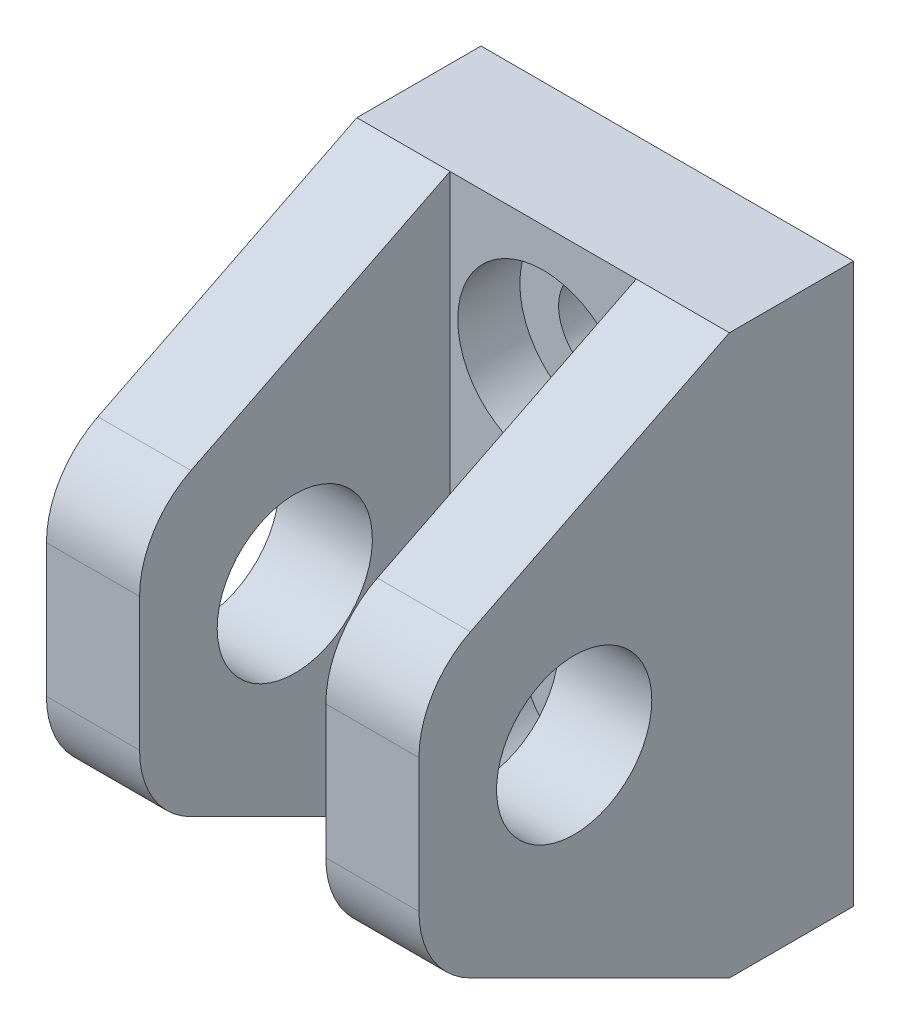
SolidWorks part; units mm, degrees
ref_plane "前视基准面" through (0, 0, 0) normal (0, 0, 1) x (1, 0, 0)
ref_plane "上视基准面" through (0, 0, 0) normal (0, 1, 0) x (1, 0, 0)
ref_plane "右视基准面" through (0, 0, 0) normal (1, 0, 0) x (0, 0, -1)
sketch "草图1" plane through (0, 0, 0) normal (0, 0, 1) x (1, 0, 0)
  line L1 (0, 0) -> (20, 0)
  line L2 (0, 0) -> (0, 18)
  line L3 (0, 18) -> (20, 18)
  line L4 (20, 0) -> (20, 18)
  dimension "D1" = 20
  dimension "D2" = 18
extrude "凸台-拉伸1" add sketch "草图1" along normal blind 4
sketch "草图2" plane through (0, 0, 4) normal (0, 0, 1) x (1, 0, 0)
  line L0 (0, 0) -> (20, 0) construction
  line L1 (16, 0) -> (13, 0)
  line L2 (16, 0) -> (16, 18)
  line L3 (16, 18) -> (13, 18)
  line L4 (13, 0) -> (13, 18)
  line L5 (20, 18) -> (0, 18) construction
  line L6 (20, 0) -> (20, 18) construction
  line L7 (7, 0) -> (4, 0)
  line L8 (7, 0) -> (7, 18)
  line L9 (7, 18) -> (4, 18)
  line L10 (4, 0) -> (4, 18)
  dimension "D1" = 6
  dimension "D2" = 3
  dimension "D3" = 3
  dimension "D4" = 4
extrude "凸台-拉伸2" add sketch "草图2" along normal blind 10
sketch "草图3" plane through (4, 0, 0) normal (-1, 0, 0) x (0, 0, 1)
  line L0 (4, 18) -> (14, 13)
  line L1 (14, 18) -> (14, 0) construction
  line L2 (14, 13) -> (14, 19.3135)
  line L3 (14, 19.3135) -> (4, 18)
  line L4 (4, 0) -> (14, 5)
  line L5 (14, 5) -> (15.3724, -0.8639)
  line L6 (15.3724, -0.8639) -> (4, 0)
  line L7 (14, 18) -> (4, 18) construction
  line L8 (14, 0) -> (4, 0) construction
  dimension "D1" = 5
  dimension "D2" = 5
extrude "切除-拉伸1" cut sketch "草图3" against normal through all
sketch "草图6" plane through (16, 0, 0) normal (1, 0, 0) x (0, 0, -1)
  line L0 (-14, 5) -> (-14, 13) construction
  circle A0 centre (-9, 9) radius 2.5
  dimension "D1" = 5
  dimension "D2" = 5
extrude "切除-拉伸2" cut sketch "草图6" against normal through all
fillet "圆角1" radius 3 4 edges at (5.5, 13, 14) (14.5, 13, 14) (5.5, 5, 14) (14.5, 5, 14)
sketch "草图9" plane through (0, 0, 4) normal (0, 0, 1) x (1, 0, 0)
  line L4 (4, 0) -> (4, 18)
  line L5 (4, 18) -> (0, 18)
  line L6 (0, 18) -> (0, 0)
  line L7 (0, 0) -> (4, 0)
  line L8 (4, 0) -> (4, 18)
  line L9 (4, 18) -> (0, 18)
  line L10 (0, 18) -> (0, 0)
  line L11 (0, 0) -> (4, 0)
  dimension "D1" = 0
extrude "切除-拉伸4" cut sketch "草图9" against normal through all
sketch "草图10" plane through (0, 0, 4) normal (0, 0, 1) x (1, 0, 0)
  line L4 (16, 18) -> (16, 0)
  line L5 (16, 0) -> (20, 0)
  line L6 (20, 0) -> (20, 18)
  line L7 (20, 18) -> (16, 18)
  line L8 (16, 18) -> (16, 0)
  line L9 (16, 0) -> (20, 0)
  line L10 (20, 0) -> (20, 18)
  line L11 (20, 18) -> (16, 18)
  dimension "D1" = 0
extrude "切除-拉伸5" cut sketch "草图10" against normal through all
sketch "草图11" plane through (0, 0, 4) normal (0, 0, 1) x (1, 0, 0)
  line L0 (13, 18) -> (7, 18) construction
  line L1 (7, 0) -> (13, 0) construction
  circle A0 centre (10, 14) radius 1.5
  circle A1 centre (10, 4) radius 1.5
  dimension "D1" = 4
  dimension "D2" = 4
extrude "切除-拉伸6" cut sketch "草图11" against normal through all
sketch "草图12" plane through (0, 0, 4) normal (0, 0, 1) x (1, 0, 0)
  circle A0 centre (10, 14) radius 2.75
  circle A1 centre (10, 4) radius 2.75
extrude "切除-拉伸7" cut sketch "草图12" against normal blind 2
